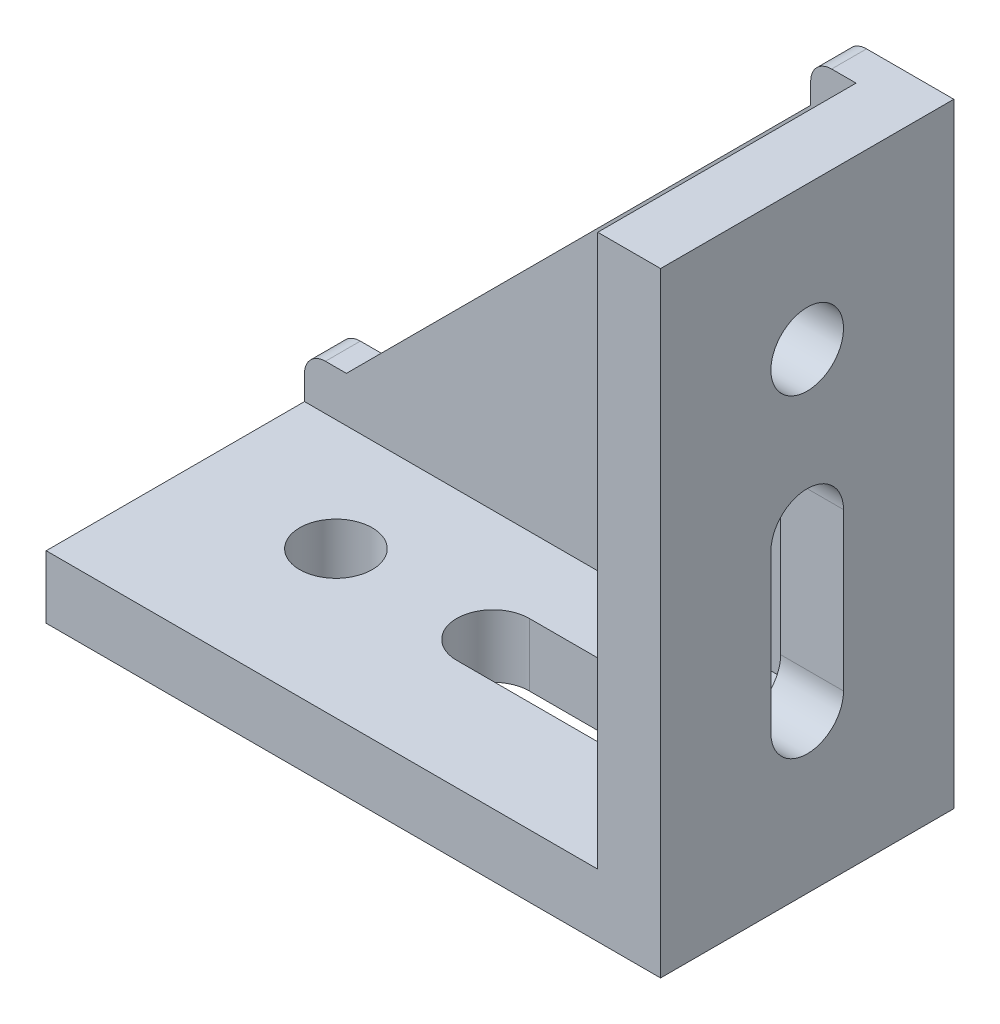
SolidWorks part; units mm, degrees
ref_plane "前视基准面" through (0, 0, 0) normal (0, 0, 1) x (1, 0, 0)
ref_plane "上视基准面" through (0, 0, 0) normal (0, 1, 0) x (1, 0, 0)
ref_plane "右视基准面" through (0, 0, 0) normal (1, 0, 0) x (0, 0, -1)
sketch "草图1" plane through (0, 0, 0) normal (0, 0, 1) x (1, 0, 0)
  line B0 (-88, 0) -> (0, 0)
  line B1 (0, 0) -> (0, 88)
  line B2 (-88, 9) -> (-9, 9)
  line B3 (-9, 9) -> (-9, 88)
  line B4 (-9, 88) -> (0, 88)
  line B5 (-88, 9) -> (-88, 0)
sketch_block_instance "A$C4E451862-1"
sketch_block "A$C4E451862"
extrude "凸台-拉伸1" add sketch "草图1" along normal mid plane 42
sketch "草图4" plane through (0, 0, -21) normal (0, 0, -1) x (-1, 0, 0)
  line L0 (88, 9) -> (88, 12.5)
  line L1 (88, 0) -> (0, 0) construction
  line L2 (85, 15.5) -> (82, 15.5)
  line L3 (82, 15.5) -> (15.5, 82)
  line L4 (15.5, 85) -> (15.5, 82)
  line L5 (9, 88) -> (12.5, 88)
  line L6 (9, 88) -> (9, 9)
  line L7 (9, 9) -> (88, 9)
  arc A0 (88, 12.5) -> (85, 15.5) centre (85, 12.5) ccw
  arc A1 (12.5, 88) -> (15.5, 85) centre (12.5, 85) cw
  point P15 (88, 15.5)
  dimension "D2" = 3
  dimension "D3" = 3
  dimension "D1" = 15.5
extrude "凸台-拉伸2" add sketch "草图4" against normal blind 5
sketch "草图5" plane through (0, 9, 0) normal (0, 1, 0) x (1, 0, 0)
  line L0 (-45, 0) -> (-22.5, 0) construction
  line L1 (-45, 5.2) -> (-22.5, 5.2)
  line L2 (-45, -5.2) -> (-22.5, -5.2)
  line L3 (-82, 21) -> (-15.5, 21) construction
  line L4 (0, -21) -> (0, 21) construction
  arc A0 (-45, 5.2) -> (-45, -5.2) centre (-45, 0) ccw
  arc A1 (-22.5, -5.2) -> (-22.5, 5.2) centre (-22.5, 0) ccw
  circle A2 centre (-67.5, 0) radius 5.2
  point P2 (-33.75, 0)
  dimension "D1" = 21
  dimension "D3" = 22.5
  dimension "D4" = 22.5
  dimension "D2" = 22.5
extrude "切除-拉伸1" cut sketch "草图5" against normal through all
ref_plane "基准面3" through (0, 0, 0) normal (-0.7071, -0.7071, 0) x (-0.7071, 0.7071, 0)
mirror "镜向1" about plane through (0, 0, 0) normal (-0.7071, -0.7071, 0) of "切除-拉伸1"
